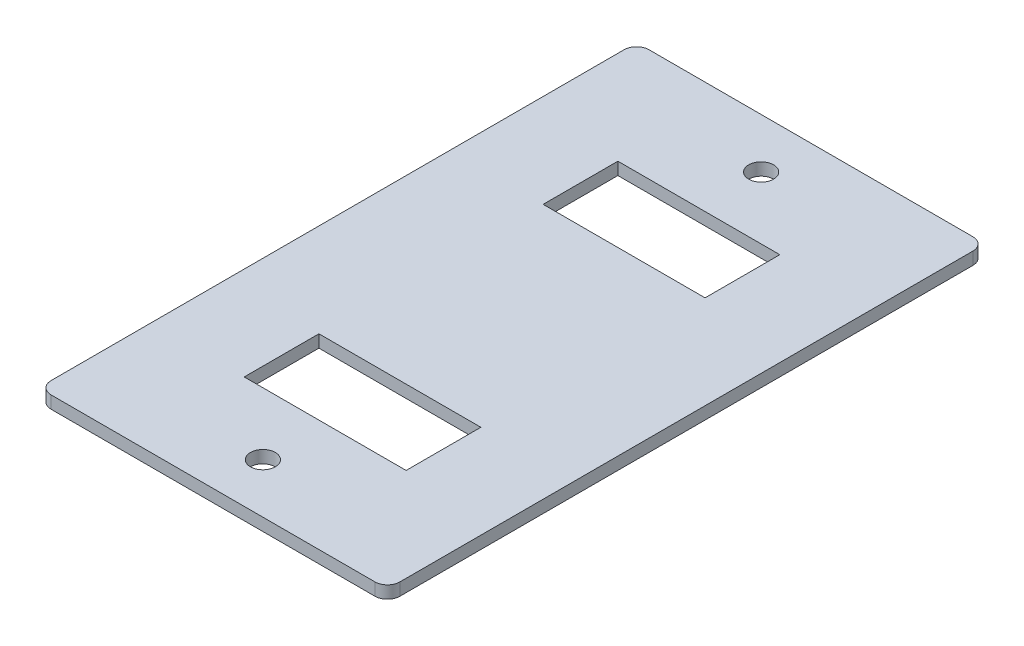
SolidWorks part; units mm, degrees
ref_plane "Alzado" through (0, 0, 0) normal (0, 0, 1) x (1, 0, 0)
ref_plane "Planta" through (0, 0, 0) normal (0, 1, 0) x (1, 0, 0)
ref_plane "Vista lateral" through (0, 0, 0) normal (1, 0, 0) x (0, 0, -1)
sketch "Croquis1" plane through (0, 0, 0) normal (0, 1, 0) x (1, 0, 0)
  line L1 (-35, 60) -> (35, 60)
  line L2 (-35, 60) -> (-35, -60)
  line L3 (-35, -60) -> (35, -60)
  line L4 (35, 60) -> (35, -60)
  line L5 (-35, 60) -> (35, -60) construction
  line L6 (-35, -60) -> (35, 60) construction
  point P0 (0, 0)
  dimension "D1" = 70
  dimension "D2" = 120
extrude "Saliente-Extruir1" add sketch "Croquis1" along normal blind 2.5
fillet "Redondeo1" radius 2.5 4 edges at (-35, 1.25, -60) (-35, 1.25, 60) (35, 1.25, -60) (35, 1.25, 60)
sketch "Croquis2" plane through (0, 2.5, 0) normal (0, 1, 0) x (1, 0, 0)
  line L0 (-35, 57.5) -> (-35, -57.5) construction
  line L1 (-16.25, 37.5) -> (16.25, 37.5)
  line L2 (-16.25, 37.5) -> (-16.25, 22.5)
  line L3 (-16.25, 22.5) -> (16.25, 22.5)
  line L4 (16.25, 37.5) -> (16.25, 22.5)
  line L5 (-16.25, 37.5) -> (16.25, 22.5) construction
  line L6 (-16.25, 22.5) -> (16.25, 37.5) construction
  line L7 (-32.5, -60) -> (32.5, -60) construction
  line L8 (-16.25, -22.5) -> (16.25, -22.5)
  line L9 (-16.25, -22.5) -> (-16.25, -37.5)
  line L10 (-16.25, -37.5) -> (16.25, -37.5)
  line L11 (16.25, -22.5) -> (16.25, -37.5)
  line L12 (-16.25, -22.5) -> (16.25, -37.5) construction
  line L13 (-16.25, -37.5) -> (16.25, -22.5) construction
  line L14 (32.5, 60) -> (-32.5, 60) construction
  point P0 (0, 30)
  point P7 (0, -30)
  dimension "D1" = 32.5
  dimension "D2" = 15
  dimension "D3" = 18.75
  dimension "D4" = 32.5
  dimension "D5" = 15
  dimension "D6" = 18.75
  dimension "D7" = 22.5
  dimension "D8" = 22.5
extrude "Cortar-Extruir1" cut sketch "Croquis2" against normal through all
sketch "Croquis3" plane through (0, 2.5, 0) normal (0, 1, 0) x (1, 0, 0)
  line L0 (-35, 57.5) -> (-35, -57.5) construction
  line L1 (-32.5, -60) -> (32.5, -60) construction
  line L2 (32.5, 60) -> (-32.5, 60) construction
  circle A0 centre (0, 50) radius 2.5
  circle A1 centre (0, -50) radius 2.5
  dimension "D1" = 5
  dimension "D2" = 5
  dimension "D3" = 35
  dimension "D4" = 35
  dimension "D5" = 10
  dimension "D6" = 10
extrude "Cortar-Extruir2" cut sketch "Croquis3" against normal through all
